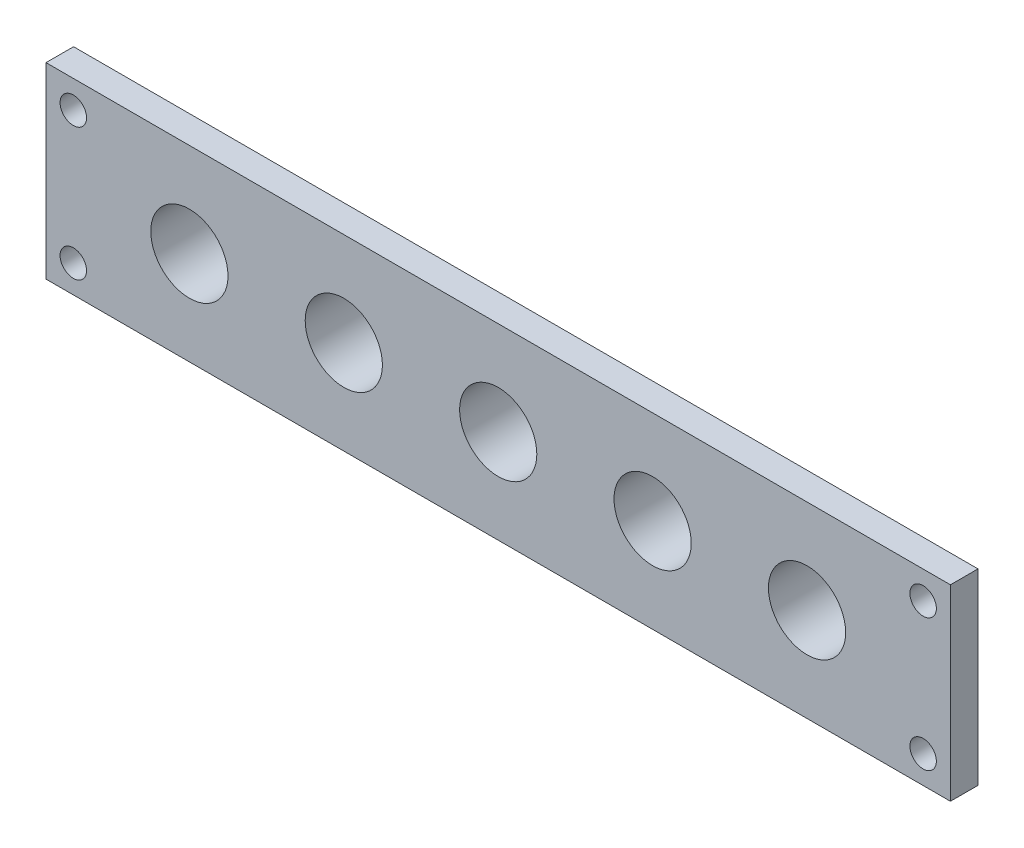
SolidWorks part; units mm, degrees
ref_plane "Спереди" through (0, 0, 0) normal (0, 0, 1) x (1, 0, 0)
ref_plane "Сверху" through (0, 0, 0) normal (0, 1, 0) x (1, 0, 0)
ref_plane "Справа" through (0, 0, 0) normal (1, 0, 0) x (0, 0, -1)
other "Configuration Table"
sketch "Эскиз1" plane through (0, 0, 0) normal (0, 0, 1) x (1, 0, 0)
  line L1 (-36.5, 4.2) -> (36.5, 4.2)
  line L2 (-36.5, 4.2) -> (-36.5, -4.2)
  line L3 (-36.5, -4.2) -> (36.5, -4.2)
  line L4 (36.5, 4.2) -> (36.5, -4.2)
  line L5 (-36.5, 4.2) -> (36.5, -4.2) construction
  line L6 (-36.5, -4.2) -> (36.5, 4.2) construction
  point P0 (0, 0)
  dimension "D1" = 8.4
  dimension "D2" = 73
extrude "Бобышка-Вытянуть1" add sketch "Эскиз1" along normal blind 3
sketch "Эскиз2" plane through (0, 0, 3) normal (0, 0, 1) x (1, 0, 0)
  line L1 (-41, 8.5) -> (41, 8.5)
  line L2 (-41, 8.5) -> (-41, -8.5)
  line L3 (-41, -8.5) -> (41, -8.5)
  line L4 (41, 8.5) -> (41, -8.5)
  line L5 (-41, 8.5) -> (41, -8.5) construction
  line L6 (-41, -8.5) -> (41, 8.5) construction
  point P0 (0, 0)
  dimension "D1" = 17
  dimension "D2" = 82
extrude "Бобышка-Вытянуть2" add sketch "Эскиз2" along normal blind 2.5
sketch "Эскиз3" plane through (0, 0, 0) normal (0, 0, -1) x (-1, 0, 0)
  circle A0 centre (0, 0) radius 3.5
  dimension "D1" = 7
extrude "Вырез-Вытянуть1" cut sketch "Эскиз3" against normal blind 10
pattern_linear "Линейный массив1" count 3 spacing 14 along (1, 0, 0) of "Вырез-Вытянуть1"
pattern_linear "Линейный массив2" count 3 spacing 14 along (-1, 0, 0) of "Вырез-Вытянуть1"
sketch "Эскиз4" plane through (0, 0, 5.5) normal (0, 0, 1) x (1, 0, 0)
  circle A0 centre (-38.5243, 5.9989) radius 1.2
  circle A1 centre (-38.5243, -5.9989) radius 1.2
  circle A2 centre (38.5243, -5.9989) radius 1.2
  circle A3 centre (38.5243, 5.9989) radius 1.2
  point P0 (0, 0)
  dimension "D1" = 2.4
  dimension "D2" = 2.4
  dimension "D3" = 2.4
  dimension "D4" = 2.4
extrude "Вырез-Вытянуть4" cut sketch "Эскиз4" against normal blind 6
equation "\"D2@Эскиз4\"=\"D1@Эскиз4\""
equation "\"D3@Эскиз4\"=\"D1@Эскиз4\""
equation "\"D4@Эскиз4\"=\"D1@Эскиз4\""
